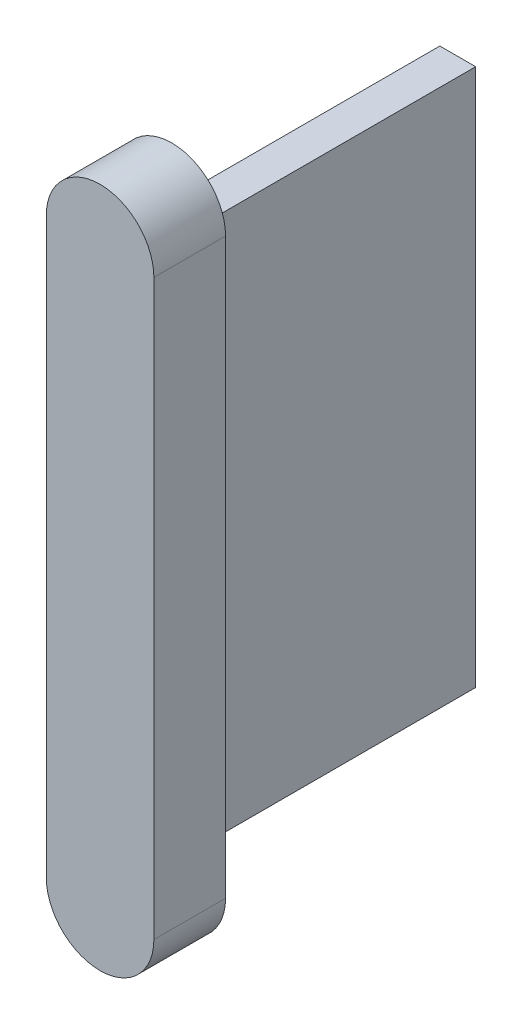
SolidWorks part; units mm, degrees
ref_plane "前视基准面" through (0, 0, 0) normal (0, 0, 1) x (1, 0, 0)
ref_plane "上视基准面" through (0, 0, 0) normal (0, 1, 0) x (1, 0, 0)
ref_plane "右视基准面" through (0, 0, 0) normal (1, 0, 0) x (0, 0, -1)
other "Configuration Table"
sketch "草图1" plane through (0, 0, 0) normal (0, 0, 1) x (1, 0, 0)
  line L0 (0, -13.6733) -> (0, -29.6733) construction
  line L1 (1.5, -13.6733) -> (1.5, -29.6733)
  line L2 (-1.5, -13.6733) -> (-1.5, -29.6733)
  arc A0 (1.5, -13.6733) -> (-1.5, -13.6733) centre (0, -13.6733) ccw
  arc A1 (-1.5, -29.6733) -> (1.5, -29.6733) centre (0, -29.6733) ccw
  point P2 (0, -21.6733)
extrude "凸台-拉伸1" add sketch "草图1" along normal blind 2 contours L2 A1 L1 A0
sketch "草图2" plane through (0, 0, 0) normal (0, 0, -1) x (-1, 0, 0)
  line L1 (-0.4777, -14.0929) -> (0.5223, -14.0929)
  line L2 (-0.4777, -14.0929) -> (-0.4777, -29.0929)
  line L3 (-0.4777, -29.0929) -> (0.5223, -29.0929)
  line L4 (0.5223, -14.0929) -> (0.5223, -29.0929)
  dimension "D1" = 15
  dimension "D2" = 1
extrude "凸台-拉伸2" add sketch "草图2" along normal blind 8
